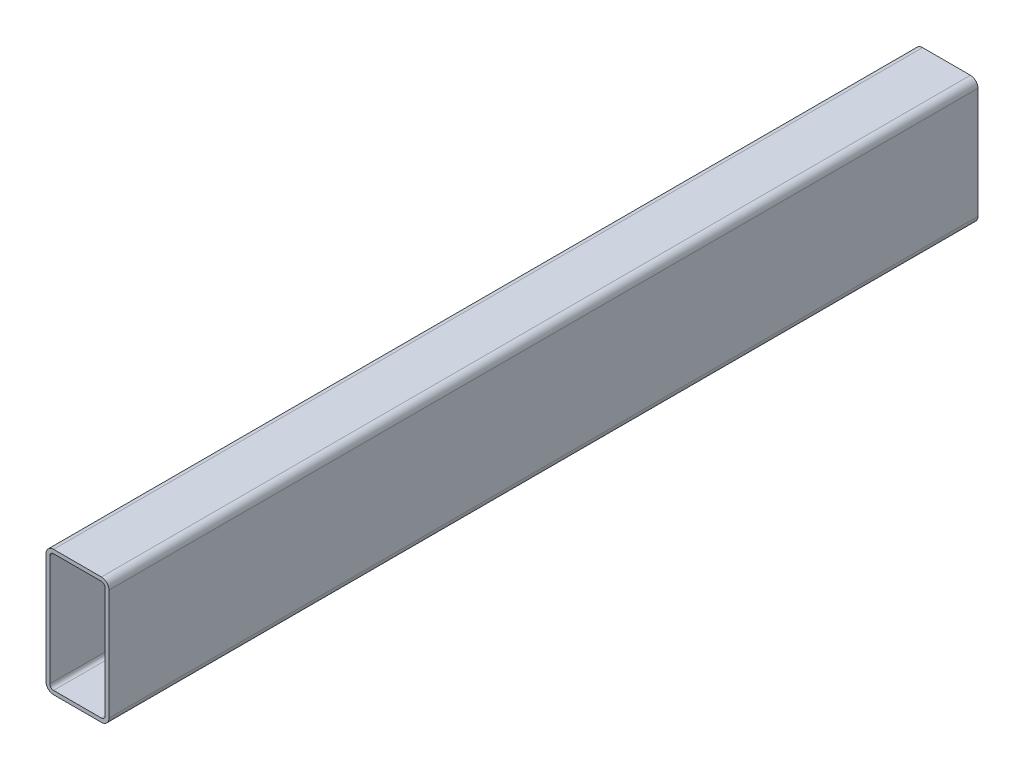
SolidWorks part; units mm, degrees
material "1.0038 (S235JRG2)"
ref_plane "Ebene vorne" through (0, 0, 0) normal (0, 0, 1) x (1, 0, 0)
ref_plane "Ebene oben" through (0, 0, 0) normal (0, 1, 0) x (1, 0, 0)
ref_plane "Ebene rechts" through (0, 0, 0) normal (1, 0, 0) x (0, 0, -1)
sketch "Skizze1" plane through (0, 0, 0) normal (0, 0, 1) x (1, 0, 0)
  line L0 (0, 0) -> (0, 67.8952) construction
  line L1 (-19, 50) -> (19, 50)
  line L2 (0, 0) -> (65.406, 0) construction
  line L3 (25, 44) -> (25, -44)
  line L4 (-25, 44) -> (-25, -44)
  line L5 (-19, -50) -> (19, -50)
  line L6 (-22, 44) -> (-22, -44)
  line L7 (-19, -47) -> (19, -47)
  line L8 (22, 44) -> (22, -44)
  line L9 (-19, 47) -> (19, 47)
  arc A0 (19, 50) -> (25, 44) centre (19, 44) cw
  arc A1 (-19, 50) -> (-25, 44) centre (-19, 44) ccw
  arc A2 (-19, -50) -> (-25, -44) centre (-19, -44) cw
  arc A3 (19, -50) -> (25, -44) centre (19, -44) ccw
  arc A4 (-19, -47) -> (-22, -44) centre (-19, -44) cw
  arc A5 (19, -47) -> (22, -44) centre (19, -44) ccw
  arc A6 (19, 47) -> (22, 44) centre (19, 44) cw
  arc A7 (-19, 47) -> (-22, 44) centre (-19, 44) ccw
  point P12 (25, 0)
  point P13 (0, 50)
  point P19 (-25, 0)
  dimension "D1" = 6
  dimension "D3" = 50
  dimension "D4" = 100
  dimension "D2" = 3
extrude "Aufsatz-Linear austragen1" add sketch "Skizze1" along normal mid plane 690
